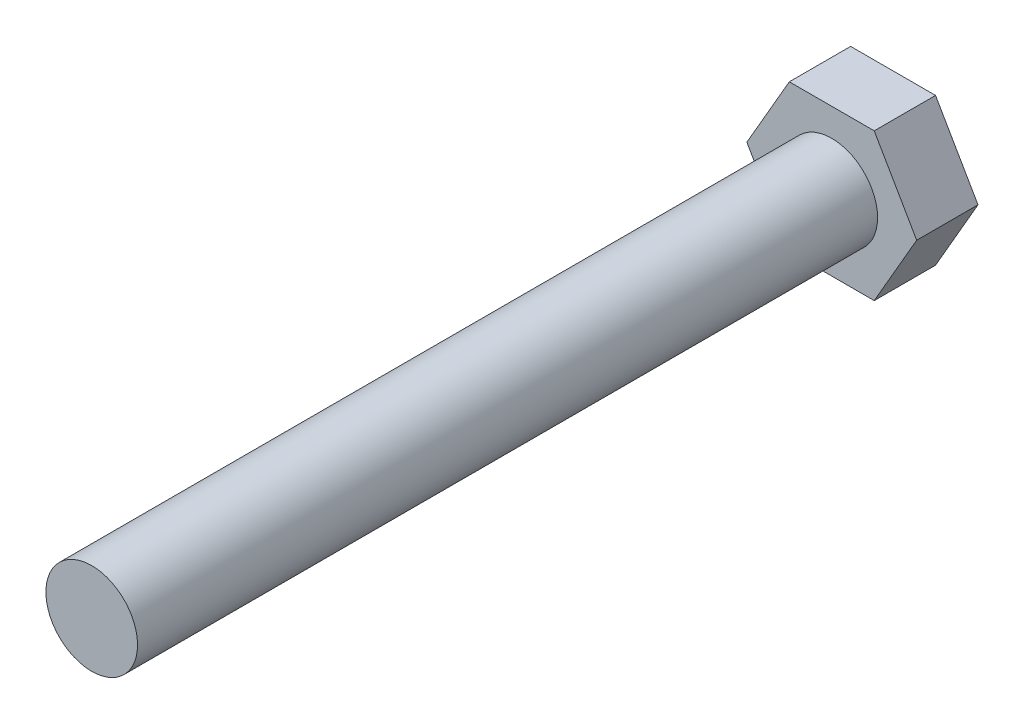
SolidWorks part; units mm, degrees
ref_plane "Front Plane" through (0, 0, 0) normal (0, 0, 1) x (1, 0, 0)
ref_plane "Top Plane" through (0, 0, 0) normal (0, 1, 0) x (1, 0, 0)
ref_plane "Right Plane" through (0, 0, 0) normal (1, 0, 0) x (0, 0, -1)
sketch "Sketch1" plane through (0, 0, 0) normal (0, 0, 1) x (1, 0, 0)
  circle A0 centre (0, 0) radius 3.9
  dimension "D1" = 7.8
extrude "Boss-Extrude1" add sketch "Sketch1" along normal blind 63 contours A0
sketch "Sketch2" plane through (0, 0, 0) normal (0, 0, -1) x (-1, 0, 0)
  line L1 (3.6142, -6.26) -> (7.2284, 0)
  line L2 (7.2284, 0) -> (3.6142, 6.26)
  line L3 (3.6142, 6.26) -> (-3.6142, 6.26)
  line L4 (-3.6142, 6.26) -> (-7.2284, 0)
  line L5 (-7.2284, 0) -> (-3.6142, -6.26)
  line L6 (-3.6142, -6.26) -> (3.6142, -6.26)
  circle A0 centre (0, 0) radius 6.26 construction
  dimension "D1" = 12.52
extrude "Boss-Extrude2" add sketch "Sketch2" along normal blind 5.22 contours L4 L5 L6 L1 L2 L3
